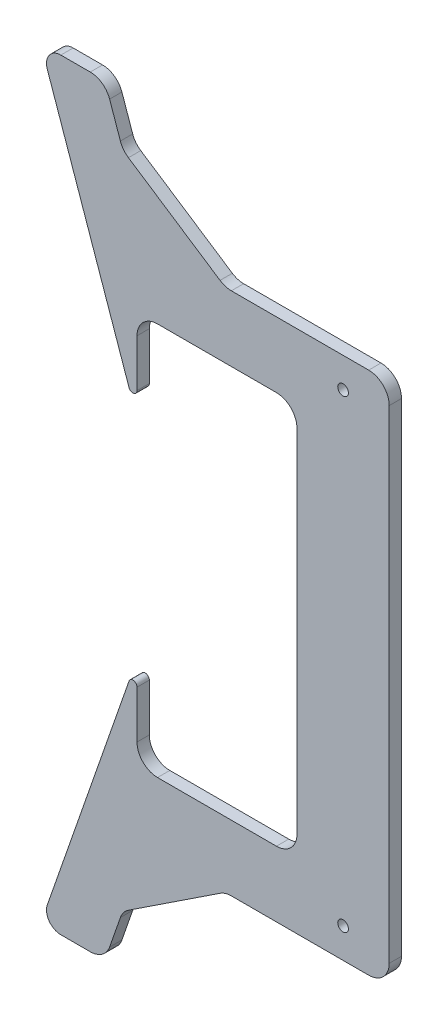
SolidWorks part; units mm, degrees
material "MDF"
ref_plane "Plano frontal" through (0, 0, 0) normal (0, 0, 1) x (1, 0, 0)
ref_plane "Plano superior" through (0, 0, 0) normal (0, 1, 0) x (1, 0, 0)
ref_plane "Plano direito" through (0, 0, 0) normal (1, 0, 0) x (0, 0, -1)
sketch "Esboço1" plane through (0, 0, 0) normal (0, 0, 1) x (1, 0, 0)
  line L0 (-22.5, 127.8) -> (-107.5, 127.8)
  line L1 (-22.5, -127.8) -> (22.5, -127.8)
  line L2 (-22.5, -127.8) -> (-22.5, 127.8)
  line L3 (-22.5, 127.8) -> (22.5, 127.8)
  line L4 (22.5, -127.8) -> (22.5, 127.8)
  line L5 (-22.5, -127.8) -> (22.5, 127.8) construction
  line L6 (-22.5, 127.8) -> (22.5, -127.8) construction
  line L7 (0, 0) -> (22.5, 0) construction
  line L8 (-147.5, 185.8) -> (-100.5, 50.8)
  line L9 (-100.5, 50.8) -> (-22.5, 50.8)
  line L10 (-107.5, 127.8) -> (-107.5, 185.8)
  line L11 (-147.5, -185.8) -> (-100.5, -50.8)
  line L12 (-100.5, -50.8) -> (-22.5, -50.8)
  line L13 (-100.5, 50.8) -> (-100.5, 95.8)
  line L14 (-100.5, 95.8) -> (-22.5, 95.8)
  line L15 (-22.5, 95.8) -> (-22.5, 50.8)
  line L16 (-22.5, -95.8) -> (-22.5, -50.8)
  line L17 (-100.5, -50.8) -> (-100.5, -95.8)
  line L18 (-100.5, -95.8) -> (-22.5, -95.8)
  line L19 (-107.5, 185.8) -> (-147.5, 185.8)
  line L20 (-107.5, -185.8) -> (-147.5, -185.8)
  line L21 (-22.5, -127.8) -> (-107.5, -127.8)
  line L22 (-107.5, -127.8) -> (-107.5, -185.8)
  line L23 (-107.5, 160.8) -> (-57.5, 127.8)
  line L24 (-107.5, -160.8) -> (-57.5, -127.8)
  line L25 (-107.5, 160.8) -> (-116.2037, 185.8)
  line L26 (-107.5, -160.8) -> (-116.2037, -185.8)
  circle A1 centre (0, 113.2) radius 2.6
  circle A2 centre (0, -113.2) radius 2.6
  point P0 (0, 0)
  point P11 (0, 127.8)
  dimension "D2" = 14.6
  dimension "D3" = 5.2
  dimension "D1" = 255.6
  dimension "D4" = 45
  dimension "D5" = 125
  dimension "D6" = 78
  dimension "D7" = 85
  dimension "D8" = 135
  dimension "D9" = 77
  dimension "D10" = 45
  dimension "D11" = 25
  dimension "D12" = 50
extrude "Ressalto-extrusão1" add sketch "Esboço1" along normal blind 6
fillet "Filete1" radius 2 2 edges at (-100.5, -50.8, 3) (-100.5, 50.8, 3)
fillet "Filete3" radius 10 12 edges at (-57.5, -127.8, 3) (-107.5, -160.8, 3) (-116.2037, -185.8, 3) (-100.5, -95.8, 3) (-22.5, -95.8, 3) (22.5, -127.8, 3) (22.5, 127.8, 3) (-22.5, 95.8, 3) (-100.5, 95.8, 3) (-57.5, 127.8, 3) (-107.5, 160.8, 3) (-116.2037, 185.8, 3)
fillet "Filete4" radius 7 2 edges at (-147.5, 185.8, 3) (-147.5, -185.8, 3)
